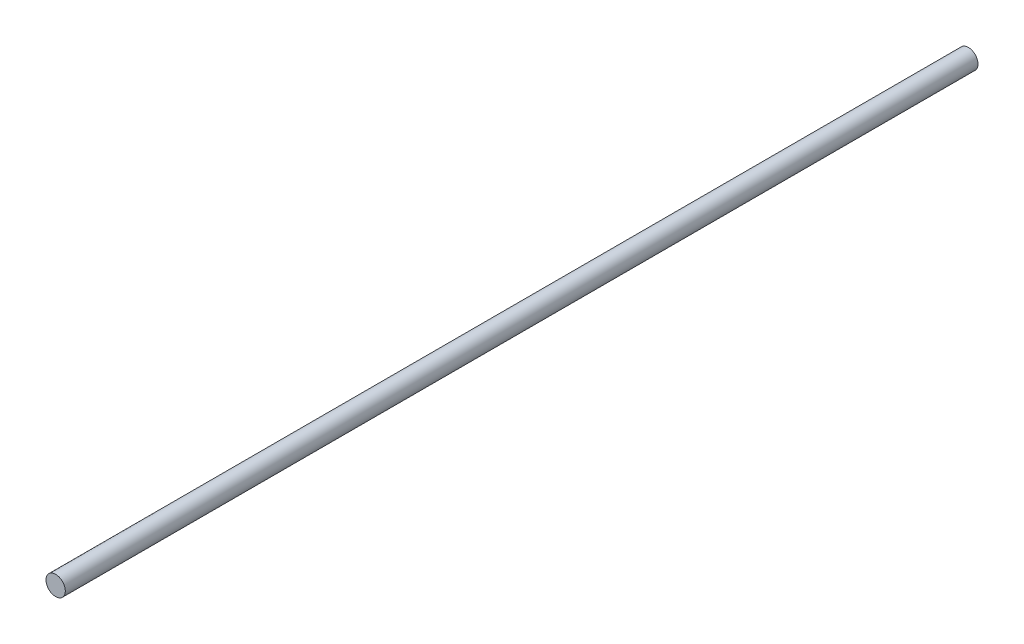
SolidWorks part; units mm, degrees
material "A-Glass Fiber"
ref_plane "Front Plane" through (0, 0, 0) normal (0, 0, 1) x (1, 0, 0)
ref_plane "Top Plane" through (0, 0, 0) normal (0, 1, 0) x (1, 0, 0)
ref_plane "Right Plane" through (0, 0, 0) normal (1, 0, 0) x (0, 0, -1)
sketch "Sketch1" plane through (0, 0, 0) normal (0, 0, 1) x (1, 0, 0)
  circle A0 centre (0, 0) radius 6.35
  dimension "D1" = 12.7
extrude "Boss-Extrude1" add sketch "Sketch1" along normal mid plane 600
